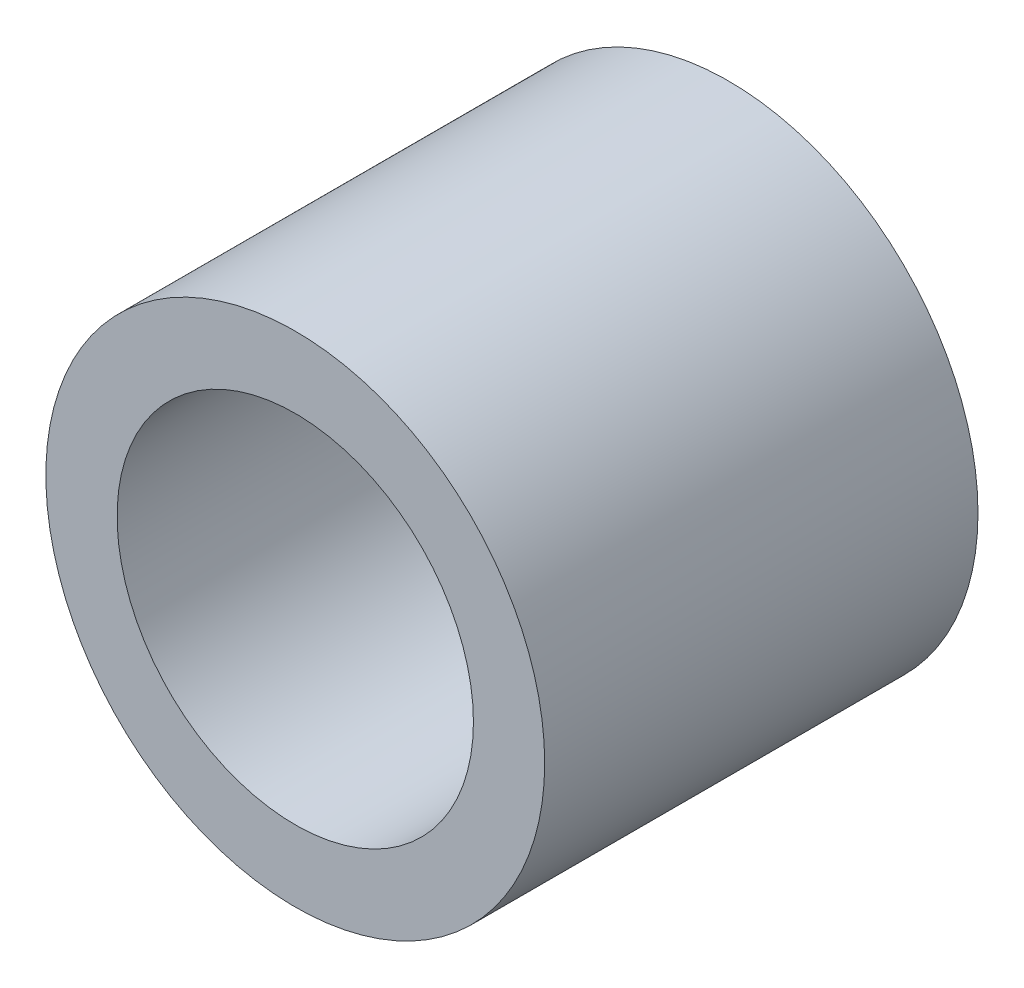
SolidWorks part; units mm, degrees
ref_plane "Front Plane" through (0, 0, 0) normal (1, 0, 0) x (0, 1, 0)
ref_plane "Top Plane" through (0, 0, 0) normal (0, 0, 1) x (0, 1, 0)
ref_plane "Right Plane" through (0, 0, 0) normal (0, 1, 0) x (-1, 0, 0)
sketch "Sketch1" plane through (0, 0, 0) normal (0, 0, 1) x (0, 1, 0)
  circle A0 centre (0, 0) radius 7.9375
  circle A1 centre (0, 0) radius 11.1125
  dimension "D1" = 15.875
  dimension "D2" = 3.175
extrude "Boss-Extrude1" add sketch "Sketch1" along normal blind 19.304
